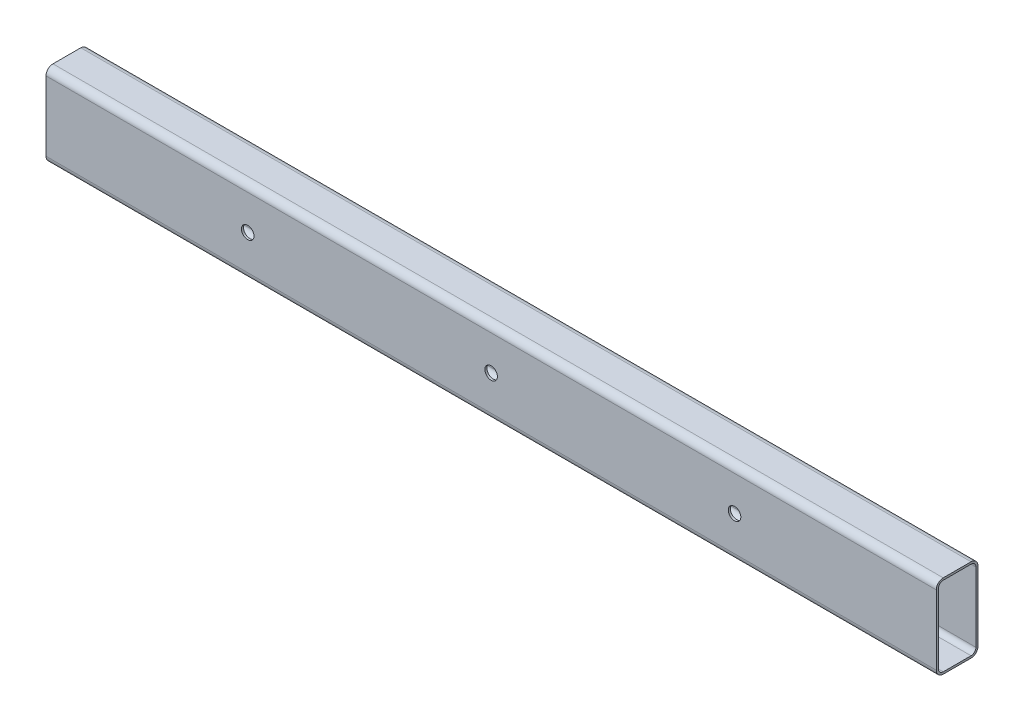
SolidWorks part; units mm, degrees
ref_plane "Front Plane" through (0, 0, 0) normal (0, 0, 1) x (1, 0, 0)
ref_plane "Top Plane" through (0, 0, 0) normal (0, 1, 0) x (1, 0, 0)
ref_plane "Right Plane" through (0, 0, 0) normal (1, 0, 0) x (0, 0, -1)
sketch "Sketch1" plane through (0, 0, 0) normal (1, 0, 0) x (0, 0, -1)
  line L1 (-20, -60) -> (20, -60)
  line L2 (-30, -50) -> (-30, 50)
  line L3 (-20, 60) -> (20, 60)
  line L4 (30, -50) -> (30, 50)
  line L5 (-30, -60) -> (30, 60) construction
  line L6 (-30, 60) -> (30, -60) construction
  arc A0 (-20, -60) -> (-30, -50) centre (-20, -50) cw
  arc A1 (20, -60) -> (30, -50) centre (20, -50) ccw
  arc A2 (30, 50) -> (20, 60) centre (20, 50) ccw
  arc A3 (-20, 60) -> (-30, 50) centre (-20, 50) ccw
  point P0 (0, 0)
  dimension "D3" = 10
  dimension "D1" = 120
  dimension "D2" = 60
extrude "Extrude-Thin1" add sketch "Sketch1" along normal blind 640 and the other way blind 640 thin thin type one direction reverse wall 3
sketch "Sketch2" plane through (0, 0, 0) normal (0, 0, 1) x (1, 0, 0)
  line L1 (0, -33) -> (0, 33) construction
  circle A0 centre (0, 0) radius 9
  circle A1 centre (-350, 0) radius 9
  circle A2 centre (350, 0) radius 9
  dimension "D1" = 18
  dimension "D2" = 350
extrude "Cut-Extrude1" cut sketch "Sketch2" against normal through all both and the other way through all
